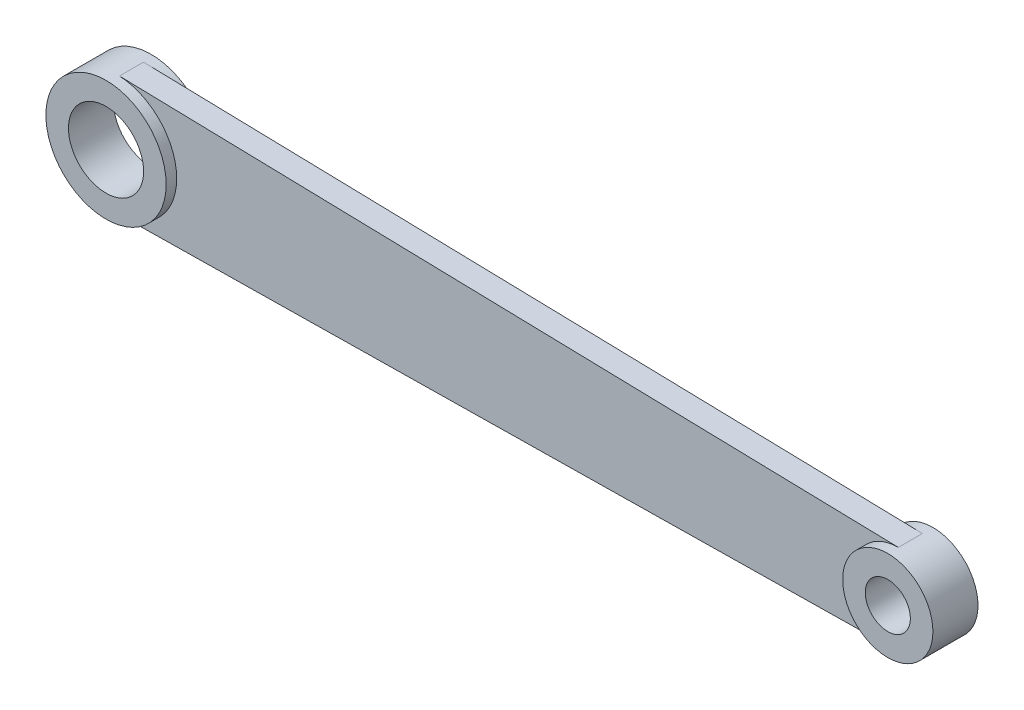
SolidWorks part; units mm, degrees
material "Cast Alloy Steel"
ref_plane "Front Plane" through (0, 0, 0) normal (0, 0, 1) x (1, 0, 0)
ref_plane "Top Plane" through (0, 0, 0) normal (0, 1, 0) x (1, 0, 0)
ref_plane "Right Plane" through (0, 0, 0) normal (1, 0, 0) x (0, 0, -1)
sketch "Sketch1" plane through (0, 0, 0) normal (0, 0, 1) x (1, 0, 0)
  line L0 (-200.1851, 20) -> (59.8149, 13.7273)
  line L1 (-200.1851, -20) -> (59.8149, -16.2727)
  circle A0 centre (-200.1851, 0) radius 20
  circle A1 centre (59.8149, -1.2727) radius 15
  dimension "D1" = 40
  dimension "D2" = 30
  dimension "D3" = 260
extrude "Boss-Extrude1" add sketch "Sketch1" along normal mid plane 8 contours A1 L0 A0 L1
ref_plane "Plane1" through (0, 0, 0) normal (0, 0, 1) x (1, 0, 0)
sketch "Sketch2" plane through (0, 0, 0) normal (0, 0, 1) x (1, 0, 0)
  circle A0 centre (-200.1851, 0) radius 20
  circle A1 centre (-200.1851, 0) radius 12.5
  circle A2 centre (59.8149, -1.2727) radius 15
  circle A3 centre (59.8149, -1.2727) radius 7.5
  dimension "D1" = 40
  dimension "D2" = 25
  dimension "D3" = 15
extrude "Boss-Extrude2" add sketch "Sketch2" along normal mid plane 15
